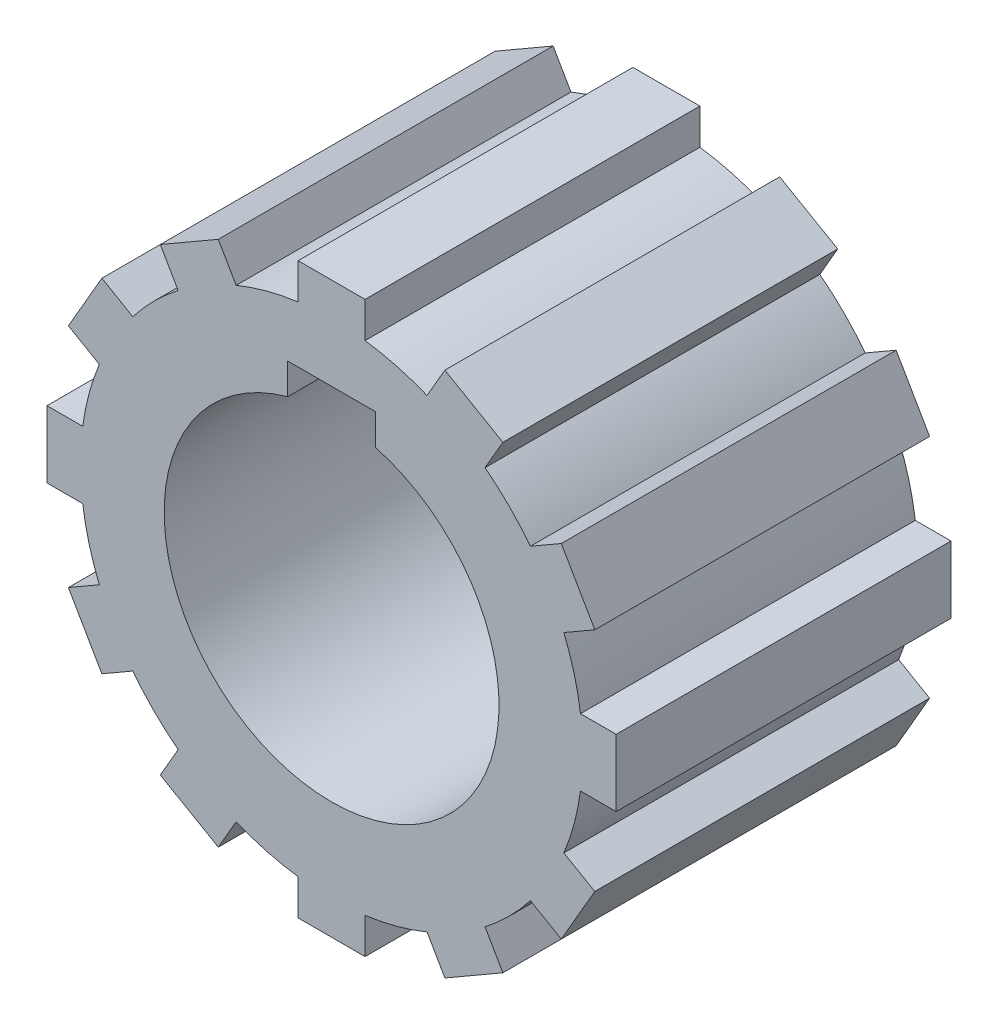
SolidWorks part; units mm, degrees
ref_plane "前视基准面" through (0, 0, 0) normal (0, 0, 1) x (1, 0, 0)
ref_plane "上视基准面" through (0, 0, 0) normal (0, 1, 0) x (1, 0, 0)
ref_plane "右视基准面" through (0, 0, 0) normal (1, 0, 0) x (0, 0, -1)
sketch "草图1" plane through (0, 0, 0) normal (0, 0, 1) x (1, 0, 0)
  line L0 (6.7679, 15.7224) -> (5.701, 13.8744)
  line L1 (-2, 17) -> (2, 17)
  line L2 (-2, 17) -> (-2, 14.8661)
  line L4 (2, 17) -> (2, 14.8661)
  line L7 (6.7679, 15.7224) -> (10.2321, 13.7224)
  line L8 (10.2321, 13.7224) -> (9.1651, 11.8744)
  line L10 (13.7224, 10.2321) -> (11.8744, 9.1651)
  line L11 (13.7224, 10.2321) -> (15.7224, 6.7679)
  line L12 (15.7224, 6.7679) -> (13.8744, 5.701)
  line L14 (17, 2) -> (14.8661, 2)
  line L15 (17, 2) -> (17, -2)
  line L16 (17, -2) -> (14.8661, -2)
  line L18 (15.7224, -6.7679) -> (13.8744, -5.701)
  line L19 (15.7224, -6.7679) -> (13.7224, -10.2321)
  line L20 (13.7224, -10.2321) -> (11.8744, -9.1651)
  line L22 (10.2321, -13.7224) -> (9.1651, -11.8744)
  line L23 (10.2321, -13.7224) -> (6.7679, -15.7224)
  line L24 (6.7679, -15.7224) -> (5.701, -13.8744)
  line L26 (2, -17) -> (2, -14.8661)
  line L27 (2, -17) -> (-2, -17)
  line L28 (-2, -17) -> (-2, -14.8661)
  line L30 (-6.7679, -15.7224) -> (-5.701, -13.8744)
  line L31 (-6.7679, -15.7224) -> (-10.2321, -13.7224)
  line L32 (-10.2321, -13.7224) -> (-9.1651, -11.8744)
  line L34 (-13.7224, -10.2321) -> (-11.8744, -9.1651)
  line L35 (-13.7224, -10.2321) -> (-15.7224, -6.7679)
  line L36 (-15.7224, -6.7679) -> (-13.8744, -5.701)
  line L38 (-17, -2) -> (-14.8661, -2)
  line L39 (-17, -2) -> (-17, 2)
  line L40 (-17, 2) -> (-14.8661, 2)
  line L42 (-15.7224, 6.7679) -> (-13.8744, 5.701)
  line L43 (-15.7224, 6.7679) -> (-13.7224, 10.2321)
  line L44 (-13.7224, 10.2321) -> (-11.8744, 9.1651)
  line L46 (-10.2321, 13.7224) -> (-9.1651, 11.8744)
  line L47 (-10.2321, 13.7224) -> (-6.7679, 15.7224)
  line L48 (-6.7679, 15.7224) -> (-5.701, 13.8744)
  arc A0 (-9.1651, 11.8744) -> (-11.8744, 9.1651) centre (0, 0) ccw
  arc A1 (-2, 14.8661) -> (-5.701, 13.8744) centre (0, 0) ccw
  arc A2 (5.701, 13.8744) -> (2, 14.8661) centre (0, 0) ccw
  arc A3 (11.8744, 9.1651) -> (9.1651, 11.8744) centre (0, 0) ccw
  arc A4 (14.8661, 2) -> (13.8744, 5.701) centre (0, 0) ccw
  arc A5 (-13.8744, 5.701) -> (-14.8661, 2) centre (0, 0) ccw
  arc A6 (-14.8661, -2) -> (-13.8744, -5.701) centre (0, 0) ccw
  arc A7 (-11.8744, -9.1651) -> (-9.1651, -11.8744) centre (0, 0) ccw
  arc A8 (-5.701, -13.8744) -> (-2, -14.8661) centre (0, 0) ccw
  arc A9 (2, -14.8661) -> (5.701, -13.8744) centre (0, 0) ccw
  arc A10 (9.1651, -11.8744) -> (11.8744, -9.1651) centre (0, 0) ccw
  arc A11 (13.8744, -5.701) -> (14.8661, -2) centre (0, 0) ccw
  point P3 (0, 15)
  dimension "D3" = 30
  dimension "D1" = 4
  dimension "D2" = 17
  dimension "D4" = 12
extrude "凸台-拉伸1" add sketch "草图1" along normal blind 20
sketch "草图2" plane through (0, 0, 20) normal (0, 0, 1) x (1, 0, 0)
  line L1 (-2.6249, 11.5) -> (2.6249, 11.5)
  line L2 (-2.6249, 11.5) -> (-2.6249, 8.5)
  line L3 (-2.6249, 8.5) -> (2.6249, 8.5)
  line L4 (2.6249, 11.5) -> (2.6249, 8.5)
  line L5 (0, 8.5) -> (0, 11.5) construction
  line L6 (-2.6249, 10) -> (2.6249, 10) construction
  circle A0 centre (0, 0) radius 10
  point P3 (0, 10)
  dimension "D1" = 20
  dimension "D2" = 1.5
extrude "切除-拉伸2" cut sketch "草图2" against normal through all contours A0 L4 L1 L2 | L2 A0 L4 L3
